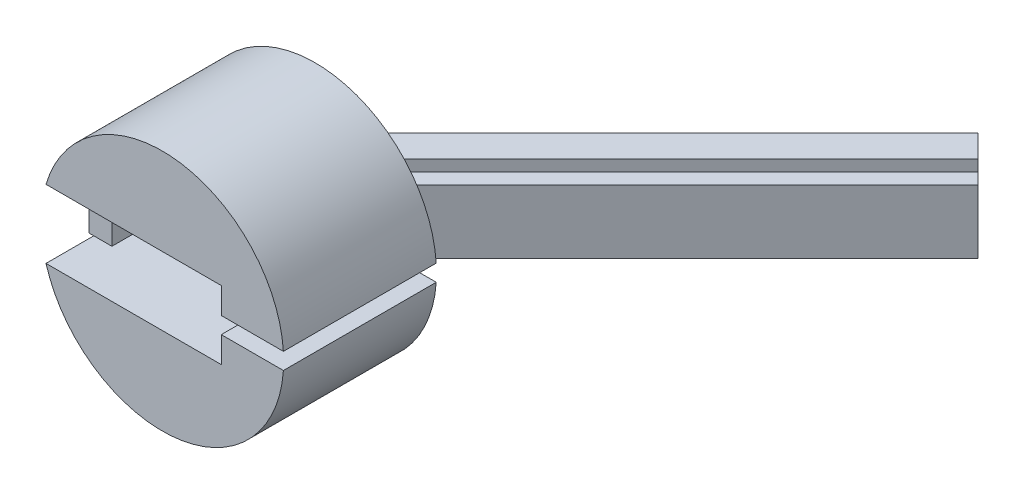
SolidWorks part; units mm, degrees
ref_plane "Front Plane" through (0, 0, 0) normal (0, 0, 1) x (1, 0, 0)
ref_plane "Top Plane" through (0, 0, 0) normal (0, 1, 0) x (1, 0, 0)
ref_plane "Right Plane" through (0, 0, 0) normal (1, 0, 0) x (0, 0, -1)
ref_plane "Plane1" through (0, 0, 15) normal (0, 0, 1) x (1, 0, 0)
sketch "Sketch5" plane through (0, 0, 15) normal (0, 0, 1) x (1, 0, 0)
  line L1 (-63.5, -63.5) -> (63.5, -63.5) construction
  line L2 (-63.5, -63.5) -> (-63.5, 63.5) construction
  line L3 (-63.5, 63.5) -> (63.5, 63.5) construction
  line L4 (63.5, -63.5) -> (63.5, 63.5) construction
  line L5 (-63.5, -63.5) -> (63.5, 63.5) construction
  line L6 (-63.5, 63.5) -> (63.5, -63.5) construction
  circle A0 centre (0, 0) radius 38.1 construction
  dimension "D1" = 76.2
  dimension "D2" = 25.4
sketch "Sketch3" plane through (0, 0, 0) normal (0, 0, 1) x (1, 0, 0)
  line L32 (10.8491, -10.7491) -> (10.8491, 10.7491)
  line L33 (-30.8491, -10.7491) -> (10.8491, -10.7491)
  line L34 (-30.8491, 10.7491) -> (-30.8491, -10.7491)
  line L35 (10.8491, 10.7491) -> (-30.8491, 10.7491)
  line L36 (10.8491, -10.7491) -> (10.8491, -4.6)
  line L37 (-30.8491, -10.7491) -> (10.8491, -10.7491)
  line L38 (-30.8491, 10.7491) -> (-30.8491, -10.7491)
  line L39 (10.8491, 10.7491) -> (-30.8491, 10.7491)
  line L40 (38.0112, 2.6) -> (12.8491, 2.6)
  line L41 (38.0112, -2.6) -> (12.8491, -2.6)
  line L42 (22.6, 2.1) -> (12.6, 2.1) construction
  line L43 (12.6, -2.1) -> (22.6, -2.1) construction
  line L44 (12.8491, 2.6) -> (10.8491, 4.6)
  line L45 (12.8491, -2.6) -> (10.8491, -4.6)
  line L47 (-38.1, -10.7491) -> (-38.1, 10.7491)
  line L48 (10.8491, 4.6) -> (10.8491, 10.7491)
  line L49 (-38.1, 10.7491) -> (-36.5522, 10.7491)
  line L51 (-38.1, -10.7491) -> (-36.5522, -10.7491)
  circle A0 centre (0, 0) radius 38.1 construction
  arc A1 (38.0112, 2.6) -> (-36.5522, 10.7491) centre (0, 0) ccw
  arc A2 (-36.5522, -10.7491) -> (38.0112, -2.6) centre (0, 0) ccw
  point P3 (-38.1, 0)
  dimension "D1" = 0.5
  dimension "D3" = 0.5
  dimension "D4" = 0.5
  dimension "D5" = 2
  dimension "D6" = 45
  dimension "D7" = 45
extrude "Boss-Extrude1" add sketch "Sketch3" against normal up to surface (28 mm away) contours A1 L49 L47 L51 A2 L41 L45 L36 L37 L38 L39 L48 L44 L40
sketch "Sketch7" plane through (0, 0, -28) normal (0, 0, -1) x (-1, 0, 0)
  line L0 (-12.8491, 2.6) -> (-12.8491, -2.6)
  line L13 (38.1, 10.7491) -> (36.5522, 10.7491)
  line L14 (38.1, 10.7491) -> (36.5522, 10.7491)
  line L15 (-38.0112, 2.6) -> (-12.8491, 2.6)
  line L16 (-12.8491, 2.6) -> (-10.8491, 4.6)
  line L17 (-10.8491, 4.6) -> (-10.8491, 10.7491)
  line L18 (-10.8491, 10.7491) -> (30.8491, 10.7491)
  line L19 (30.8491, 10.7491) -> (30.8491, -10.7491)
  line L20 (30.8491, -10.7491) -> (-10.8491, -10.7491)
  line L21 (-10.8491, -10.7491) -> (-10.8491, -4.6)
  line L22 (-10.8491, -4.6) -> (-12.8491, -2.6)
  line L23 (-12.8491, -2.6) -> (-38.0112, -2.6)
  line L24 (36.5522, -10.7491) -> (38.1, -10.7491)
  line L25 (36.5522, -10.7491) -> (38.1, -10.7491)
  line L26 (38.1, -10.7491) -> (38.1, 10.7491)
  line L27 (38.1, -10.7491) -> (38.1, 10.7491)
  line L29 (-38.0112, 2.6) -> (-12.8491, 2.6)
  line L37 (-12.8491, -2.6) -> (-38.0112, -2.6)
  arc A2 (36.5522, 10.7491) -> (-38.0112, 2.6) centre (0, 0) ccw
  arc A3 (36.5522, 10.7491) -> (-38.0112, 2.6) centre (0, 0) ccw
  arc A4 (-38.0112, -2.6) -> (36.5522, -10.7491) centre (0, 0) ccw
  arc A5 (-38.0112, -2.6) -> (36.5522, -10.7491) centre (0, 0) ccw
  dimension "D1" = 0
extrude "Boss-Extrude5" add sketch "Sketch7" along normal blind 5
sketch "Sketch8" plane through (0, 0, 0) normal (0, 1, 0) x (1, 0, 0)
  line L0 (-3.9579, 33) -> (102.1082, 139.066)
  line L2 (102.1082, 139.066) -> (95.0371, 146.1371)
  line L3 (95.0371, 146.1371) -> (-18.1, 33)
  line L4 (-18.1, 33) -> (-3.9579, 33)
  line L5 (38.0112, 33) -> (-36.5522, 33) construction
  dimension "D1" = 45
  dimension "D2" = 10
  dimension "D3" = 150
  dimension "D4" = 20
extrude "Boss-Extrude6" add sketch "Sketch8" along normal mid plane 20
sketch "Sketch9" plane through (120.5871, 0, -120.5871) normal (0.7071, 0, -0.7071) x (-0.7071, 0, -0.7071)
  line L0 (26.1332, 5) -> (21.1332, 5)
  line L1 (26.1332, 10) -> (26.1332, -10) construction
  line L2 (21.1332, 5) -> (21.1332, 10)
  line L3 (21.1332, 10) -> (16.1332, 10)
  line L4 (16.1332, 10) -> (16.1332, -10)
  line L5 (16.1332, -10) -> (21.1332, -10)
  line L6 (21.1332, -10) -> (21.1332, -5)
  line L7 (21.1332, -5) -> (26.1332, -5)
  line L8 (26.1332, 10) -> (26.1332, -10) construction
  line L9 (36.1332, 10) -> (26.1332, 10) construction
  line L10 (26.1332, -10) -> (36.1332, -10) construction
  line L11 (26.1332, 5) -> (26.1332, -5)
  dimension "D1" = 10
  dimension "D2" = 10
extrude "Boss-Extrude7" add sketch "Sketch9" against normal up to surface (150 mm away)
sketch "Sketch12" plane through (0, 0, 0) normal (0, 0, 1) x (1, 0, 0)
  line L0 (-36.5522, 10.7491) -> (18.5, 10.7491)
  line L1 (18.5, 10.7491) -> (18.5, 2.6)
  line L2 (38.0112, 2.6) -> (12.8491, 2.6) construction
  line L3 (18.5, 2.6) -> (38.0112, 2.6)
  line L4 (-36.5522, -10.7491) -> (18.5, -10.7491)
  line L5 (18.5, -10.7491) -> (18.5, -2.6)
  line L6 (38.0112, -2.6) -> (12.8491, -2.6) construction
  line L7 (18.5, -2.6) -> (38.0112, -2.6)
  line L8 (17, -9) -> (17, -6.5) construction
  arc A0 (-36.5522, -10.7491) -> (38.0112, -2.6) centre (0, 0) ccw construction
  arc A1 (38.0112, 2.6) -> (-36.5522, 10.7491) centre (0, 0) ccw construction
  arc A2 (-36.5522, -10.7491) -> (38.0112, -2.6) centre (0, 0) ccw
  arc A3 (38.0112, 2.6) -> (-36.5522, 10.7491) centre (0, 0) ccw
  dimension "D1" = 1.5
extrude "Boss-Extrude8" add sketch "Sketch12" along normal blind 15
